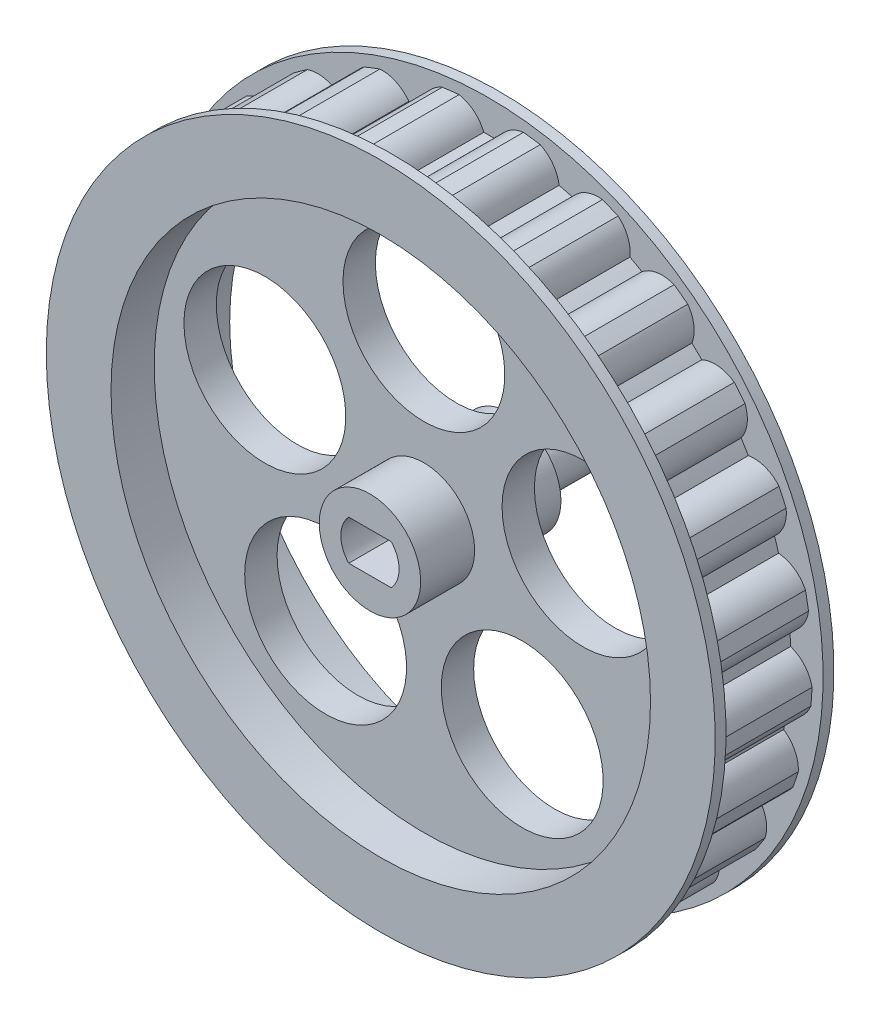
SolidWorks part; units mm, degrees
ref_plane "Front Plane" through (0, 0, 0) normal (0, 0, 1) x (1, 0, 0)
ref_plane "Top Plane" through (0, 0, 0) normal (0, 1, 0) x (1, 0, 0)
ref_plane "Right Plane" through (0, 0, 0) normal (1, 0, 0) x (0, 0, -1)
sketch "Sketch1" plane through (0, 0, 0) normal (1, 0, 0) x (0, 0, -1)
  line L0 (-3.0542, 0) -> (3.0542, 0)
  line L1 (-1.5, 2.7) -> (1.5, 2.7)
  line L2 (1.5, 2.7) -> (1.5, 25)
  line L3 (1.5, 25) -> (4.5, 25)
  line L4 (4.5, 25) -> (4.5, 30)
  line L5 (4.5, 30) -> (-4.5, 30)
  line L6 (-4.5, 30) -> (-4.5, 25)
  line L7 (-4.5, 25) -> (-1.5, 25)
  line L8 (-1.5, 25) -> (-1.5, 2.7)
  point P4 (0, 0)
  point P8 (0, 2.7)
  dimension "D1" = 3
  dimension "D2" = 30
  dimension "D3" = 2.7
  dimension "D4" = 9
  dimension "D5" = 3
  dimension "D6" = 1.5
  dimension "D7" = 5
revolve "Revolve1" add sketch "Sketch1" angle 360 about L0
sketch "Sketch2" plane through (0, 0, -4.5) normal (0, 0, -1) x (-1, 0, 0)
  circle A3 centre (0, 0) radius 30 construction
  arc A4 (0.45, 27.9964) -> (-0.8174, 27.9881) centre (0, 0) ccw
  arc A5 (2.7378, 29.8748) -> (-3.2221, 29.8265) centre (0, 0) ccw
  arc A6 (-3.2221, 29.8265) -> (-0.8174, 27.9881) centre (-3.5929, 26.8495) cw
  arc A7 (0.45, 27.9964) -> (2.7378, 29.8748) centre (3.3068, 26.8495) cw
  circle A8 centre (0, 0) radius 25 construction
  dimension "D1" = 3
  dimension "D2" = 3
extrude "Cut-Extrude1" cut sketch "Sketch2" against normal through all
pattern_circular "CirPattern1" count 25 over 360 about axis through (0, 0, 0) along (0, 0, 1) of "Cut-Extrude1"
sketch "Sketch3" plane through (0, 0, -1.5) normal (0, 0, -1) x (-1, 0, 0)
  circle A0 centre (0, 15.5) radius 7.5
  dimension "D1" = 15
  dimension "D2" = 15.5
  dimension "D3" = 0
extrude "Cut-Extrude2" cut sketch "Sketch3" against normal through all
pattern_circular "CirPattern2" count 5 over 360 about axis through (0, 0, 0) along (0, 0, 1) of "Cut-Extrude2"
sketch "Sketch4" plane through (0, 0, -4.5) normal (0, 0, -1) x (-1, 0, 0)
  circle A0 centre (0, 0) radius 31
  circle A1 centre (0, 0) radius 25
  circle A2 centre (0, 0) radius 25 construction
  arc A3 (29.5653, 5.0886) -> (29.2587, 6.628) centre (0, 0) ccw construction
  dimension "D1" = 0
  dimension "D2" = 0
  dimension "D3" = 1
extrude "Boss-Extrude1" add sketch "Sketch4" along normal blind 1
sketch "Sketch5" plane through (0, 0, -1.5) normal (0, 0, -1) x (-1, 0, 0)
  circle A0 centre (0, 0) radius 2.7
  circle A1 centre (0, 0) radius 4.7
  circle A2 centre (0, 0) radius 2.7 construction
  dimension "D1" = 0
  dimension "D2" = 2
extrude "Boss-Extrude2" add sketch "Sketch5" along normal blind 5
mirror "Mirror2" about plane through (0, 0, 0) normal (0, 0, 1) of "Boss-Extrude2"
mirror "Mirror3" about plane through (0, 0, 0) normal (0, 0, 1) of "Boss-Extrude1"
sketch "Sketch6" plane through (0, 0, -6.5) normal (0, 0, -1) x (-1, 0, 0)
  line L0 (-1.9666, 1.85) -> (1.9666, 1.85)
  line L1 (-1.9666, -1.85) -> (1.9666, -1.85)
  circle A0 centre (0, 0) radius 2.7 construction
  arc A1 (1.9666, 1.85) -> (-1.9666, 1.85) centre (0, 0) ccw
  arc A2 (1.9666, -1.85) -> (-1.9666, -1.85) centre (0, 0) cw
  dimension "D1" = 3.7
  dimension "D2" = 1.85
extrude "Boss-Extrude3" add sketch "Sketch6" against normal through all
sketch "Sketch7" plane through (0, 0, -6.5) normal (0, 0, -1) x (-1, 0, 0)
  circle A0 centre (0, 0) radius 2.7
extrude "Boss-Extrude4" add sketch "Sketch7" along normal blind 8 and the other way blind 3.6
